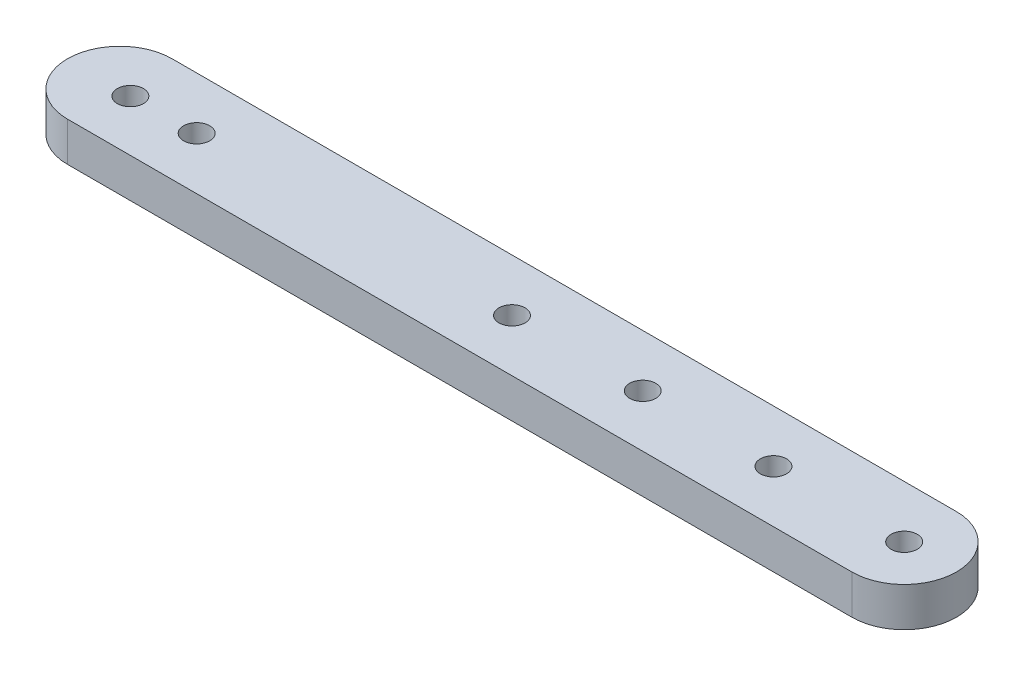
SolidWorks part; units mm, degrees
material "Plain Carbon Steel"
ref_plane "Front Plane" through (0, 0, 0) normal (0, 0, 1) x (1, 0, 0)
ref_plane "Top Plane" through (0, 0, 0) normal (0, 1, 0) x (1, 0, 0)
ref_plane "Right Plane" through (0, 0, 0) normal (1, 0, 0) x (0, 0, -1)
sketch "Sketch1" plane through (0, 0, 0) normal (0, 1, 0) x (1, 0, 0)
  line L0 (-56.2508, 0) -> (60, 0) construction
  line L1 (-60, -8) -> (60, -8)
  line L3 (-60, 8) -> (60, 8)
  line L11 (0, 8) -> (0, -8) construction
  circle A2 centre (-58.2458, -0.141) radius 2
  circle A3 centre (60, 0) radius 2
  circle A4 centre (20, 0) radius 2
  arc A5 (-60, 8) -> (-60, -8) centre (-60, 0) ccw
  arc A7 (60, -8) -> (60, 8) centre (60, 0) ccw
  circle A8 centre (-48.2458, 0) radius 2
  circle A9 centre (40, 0) radius 2
  circle A10 centre (0, 0) radius 2
  point P0 (0, 0)
  point P17 (0, 0)
  dimension "D3" = 4
  dimension "D4" = 4
  dimension "D5" = 4
  dimension "D8" = 16
  dimension "D9" = 4
  dimension "D11" = 4
  dimension "D12" = 4
  dimension "D15" = 8
  dimension "D16" = 8
  dimension "D1" = 120
  dimension "D2" = 8
  dimension "D6" = 60
  dimension "D7" = 40
  dimension "D10" = 10
  dimension "D13" = 20
  dimension "D14" = 20
extrude "Boss-Extrude1" add sketch "Sketch1" along normal blind 6
